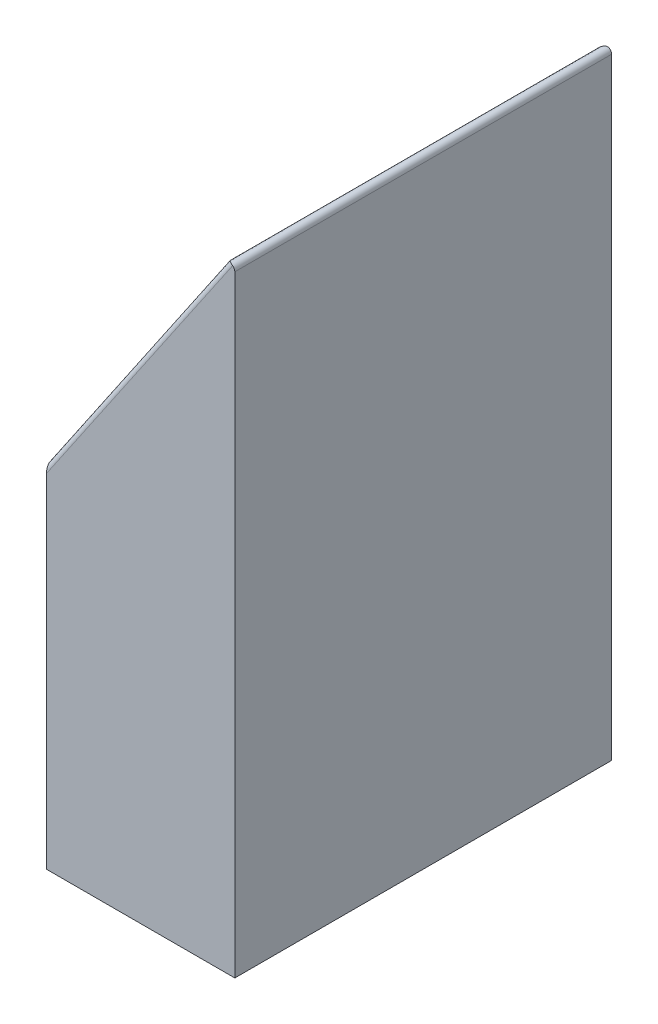
SolidWorks part; units mm, degrees
ref_plane "前基準面" through (0, 0, 0) normal (0, 0, 1) x (1, 0, 0)
ref_plane "上基準面" through (0, 0, 0) normal (0, 1, 0) x (1, 0, 0)
ref_plane "右基準面" through (0, 0, 0) normal (1, 0, 0) x (0, 0, -1)
sketch "草圖1" plane through (0, 0, 0) normal (0, 0, 1) x (1, 0, 0)
  line L0 (0, 0) -> (-150, -220)
  line L1 (-150, -220) -> (-150, -500)
  line L2 (-150, -500) -> (0, -500)
  line L3 (0, -500) -> (0, 0)
  dimension "D1" = 150
  dimension "D2" = 500
  dimension "D3" = 280
extrude "填料-伸長1" add sketch "草圖1" along normal blind 300
fillet "圓角1" radius 4 4 edges at (-75, -110, 0) (-150, -220, 150) (-75, -110, 300) (0, 0, 150)
